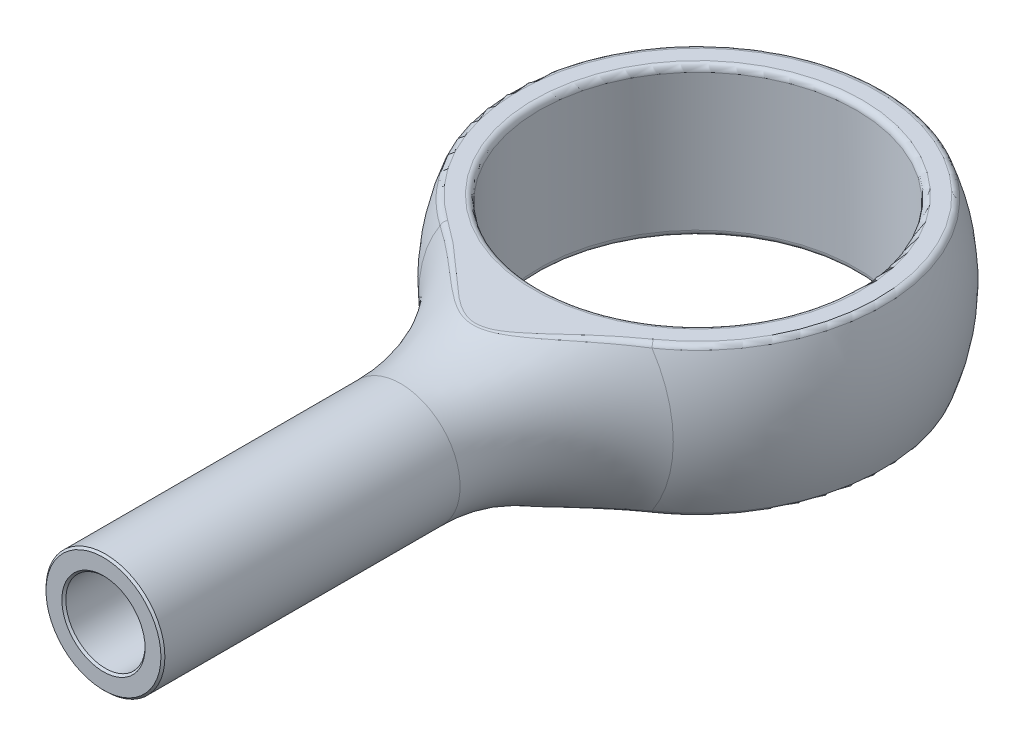
SolidWorks part; units mm, degrees
ref_plane "Front Plane" through (0, 0, 0) normal (0, 0, 1) x (1, 0, 0)
ref_plane "Top Plane" through (0, 0, 0) normal (0, 1, 0) x (1, 0, 0)
ref_plane "Right Plane" through (0, 0, 0) normal (1, 0, 0) x (0, 0, -1)
sketch "Sketch1" plane through (0, 0, 0) normal (0, 1, 0) x (1, 0, 0)
  line L0 (-1.5, -15) -> (1.5, -15)
  line L1 (-1.5, -15) -> (-1.5, -7.5)
  line L2 (1.5, -15) -> (1.5, -7.5)
  circle A0 centre (0, 0) radius 5
  circle A1 centre (0, 0) radius 4
  circle A2 centre (0, 0) radius 2 construction
  arc A3 (1.5, -7.5) -> (3.2117, -3.8321) centre (6.2857, -7.5) cw
  arc A4 (-1.5, -7.5) -> (-3.2117, -3.8321) centre (-6.2857, -7.5) ccw
  point P7 (0, -15)
  dimension "D1" = 10
  dimension "D2" = 8
  dimension "D3" = 4
  dimension "D4" = 15
  dimension "D5" = 3
  dimension "D6" = 7.5
sketch "Sketch2" plane through (0, 0, 0) normal (0, 1, 0) x (1, 0, 0)
  line L0 (-1.5, -15) -> (1.5, -15) construction
  line L1 (-1.5, -15) -> (-1.5, -7.5) construction
  line L2 (-1.5, -15) -> (0, -15)
  line L3 (-1.5, -15) -> (-1.5, -7.5)
  line L4 (0, 5) -> (0, -15)
  arc A0 (-1.5, -7.5) -> (-3.2117, -3.8321) centre (-6.2857, -7.5) ccw construction
  circle A1 centre (0, 0) radius 5 construction
  arc A2 (-1.5, -7.5) -> (-3.2117, -3.8321) centre (-6.2857, -7.5) ccw
  arc A3 (0, 5) -> (-3.2117, -3.8321) centre (0, 0) ccw
revolve "Revolve1" add sketch "Sketch2" angle 360 about L4
sketch "Sketch3" plane through (0, 0, 0) normal (1, 0, 0) x (0, 0, -1)
  line L0 (-16.42, 7.5344) -> (5.1152, 7.5344)
  line L1 (5.1152, 7.5344) -> (5.1152, 1.875)
  line L2 (5.1152, 1.875) -> (-6.761, 1.875)
  line L3 (-9.6289, 2.7792) -> (-16.42, 7.5344)
  line L4 (0, 0) -> (13.8398, 0) construction
  line L5 (2, 0) -> (-2, 0) construction
  line L6 (-9.6289, -2.7792) -> (-16.42, -7.5344)
  line L7 (5.1152, -1.875) -> (-6.761, -1.875)
  line L8 (5.1152, -7.5344) -> (5.1152, -1.875)
  line L9 (-16.42, -7.5344) -> (5.1152, -7.5344)
  arc A0 (-6.761, 1.875) -> (-9.6289, 2.7792) centre (-6.761, 6.875) cw
  arc A1 (-6.761, -1.875) -> (-9.6289, -2.7792) centre (-6.761, -6.875) ccw
  point P10 (-18.7043, 13.1651)
  point P11 (-12.7691, 12.6867)
  point P18 (-15.9575, 6.875)
  point P19 (-16.42, 7.5344)
  dimension "D1" = 5
  dimension "D2" = 145
  dimension "D3" = 3.75
extrude "Cut-Extrude1" cut sketch "Sketch3" against normal through all both and the other way through all
sketch "Sketch4" plane through (0, 0, 0) normal (0, 1, 0) x (1, 0, 0)
  circle A0 centre (0, 0) radius 4 construction
  circle A1 centre (0, 0) radius 4
extrude "Cut-Extrude2" cut sketch "Sketch4" against normal through all both and the other way through all
fillet "Fillet1" radius 0.15 6 edges at (0, 1.875, 4) (0, -1.875, 4) (0, -1.875, -4.6351) (0, 1.875, -4.6351) (0.1839, -1.875, 5.6217) (-0.1839, 1.875, 5.6217)
sketch "Sketch5" plane through (0, 0, 15) normal (0, 0, 1) x (1, 0, 0)
  circle A0 centre (0, 0) radius 1
  dimension "D1" = 2
extrude "Cut-Extrude4" cut sketch "Sketch5" against normal blind 5
chamfer "Chamfer1" distance 0.05 angle 45 2 edges at (-1.5, 0, 15) (1, 0, 15)
